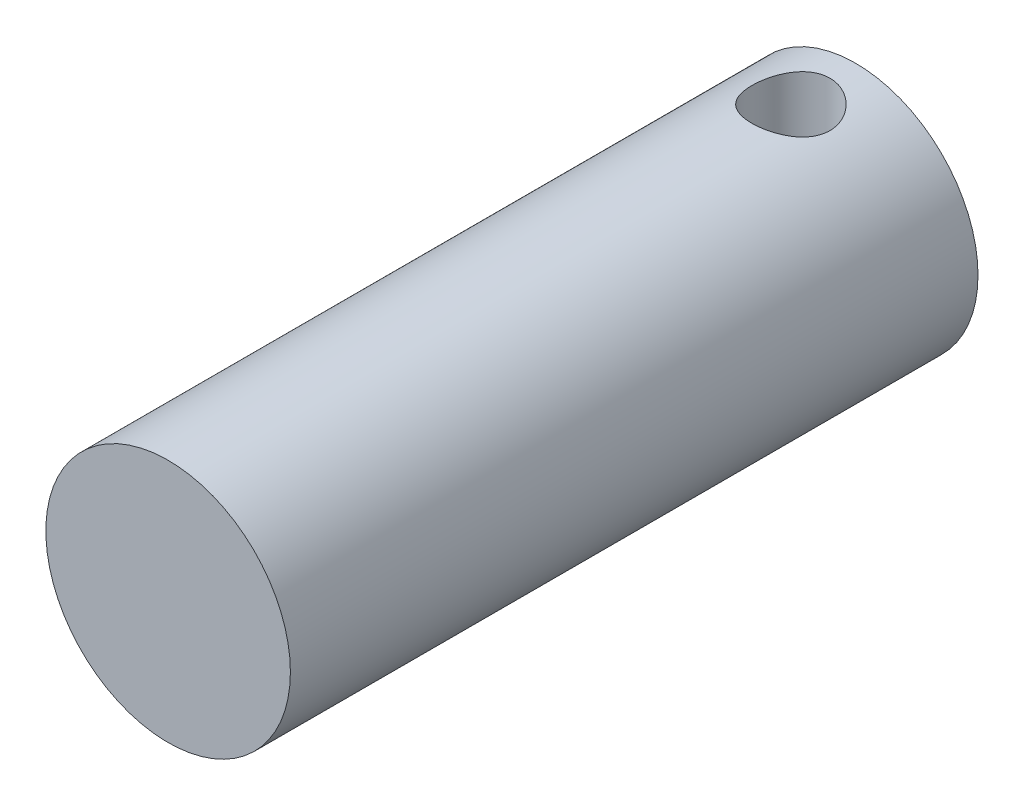
SolidWorks part; units mm, degrees
ref_plane "Front Plane" through (0, 0, 0) normal (0, 0, 1) x (1, 0, 0)
ref_plane "Top Plane" through (0, 0, 0) normal (0, 1, 0) x (1, 0, 0)
ref_plane "Right Plane" through (0, 0, 0) normal (1, 0, 0) x (0, 0, -1)
sketch "Sketch1" plane through (0, 0, 0) normal (0, 0, 1) x (1, 0, 0)
  circle A0 centre (0, 0) radius 3.975
  dimension "D1" = 7.95
extrude "Boss-Extrude1" add sketch "Sketch1" along normal mid plane 22.352
sketch "Sketch2" plane through (0, 0, 0) normal (0, 1, 0) x (1, 0, 0)
  line L0 (3.975, 11.176) -> (-3.975, 11.176) construction
  circle A0 centre (0, 9.0678) radius 1.27
  dimension "D1" = 2.54
  dimension "D2" = 2.1082
extrude "Cut-Extrude1" cut sketch "Sketch2" against normal mid plane 12.7
